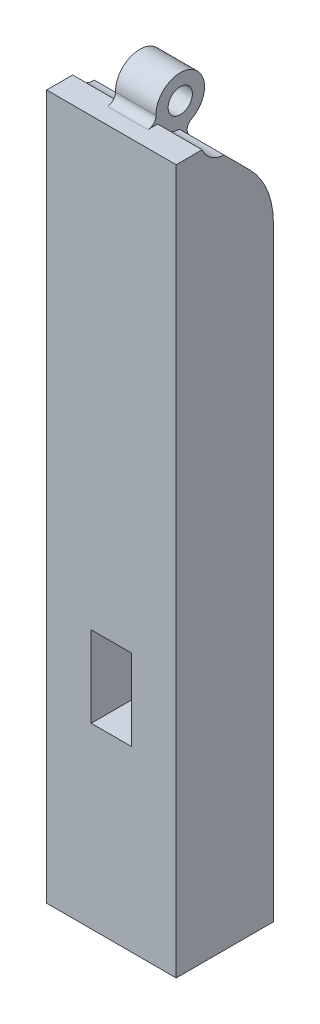
SolidWorks part; units mm, degrees
ref_plane "Front Plane" through (0, 0, 0) normal (0, 0, 1) x (1, 0, 0)
ref_plane "Top Plane" through (0, 0, 0) normal (0, 1, 0) x (1, 0, 0)
ref_plane "Right Plane" through (0, 0, 0) normal (1, 0, 0) x (0, 0, -1)
sketch "Sketch1" plane through (0, 0, 0) normal (0, 0, 1) x (1, 0, 0)
  line L1 (-8, 23.9082) -> (8, 23.9082)
  line L2 (-8, 23.9082) -> (-8, -63.0918)
  line L3 (-8, -63.0918) -> (8, -63.0918)
  line L4 (8, 23.9082) -> (8, -63.0918)
  point P4 (0, 23.9082)
extrude "Boss-Extrude2" add sketch "Sketch1" along normal blind 12
sketch "Sketch2" plane through (0, 0, 0) normal (1, 0, 0) x (0, 0, -1)
  line L0 (-12, 23.9082) -> (-8, 23.9082)
  line L1 (-12, 23.9082) -> (0, 23.9082) construction
  line L2 (0, -63.0918) -> (0, 23.9082) construction
  line L7 (-8, 23.9082) -> (0, 15.9082)
  line L8 (0, 15.9082) -> (0, 23.9082)
  line L9 (0, 23.9082) -> (-8, 23.9082)
extrude "Cut-Extrude1" cut sketch "Sketch2" against normal through all both and the other way through all contours L8 L9 L7
sketch "Sketch3" plane through (0, 0, 0) normal (1, 0, 0) x (0, 0, -1)
  line L0 (-12, 23.9082) -> (0, 23.9082)
  line L1 (-6, 23.9082) -> (-6, 25.0082)
  circle A0 centre (-6, 25.0082) radius 1.5
  circle A1 centre (-6, 25.0082) radius 3
extrude "Cut-Extrude2" cut sketch "Sketch3" against normal through all both and the other way through all contours L0 A1 A0 | L0 A1 A0
sketch "Sketch4" plane through (0, 0, 0) normal (1, 0, 0) x (0, 0, -1)
  circle A0 centre (-6, 25.0082) radius 1.5
  circle A1 centre (-6, 25.0082) radius 3
extrude "Boss-Extrude3" add sketch "Sketch4" along normal mid plane 5
fillet "Fillet1" radius 1 2 edges at (0, 23.9082, 8.7911) (0, 22.0099, 6.1017)
fillet "Fillet2" radius 10 1 edges at (0, 15.9082, 0)
sketch "Sketch5" plane through (0, 0, 0) normal (0, 0, -1) x (-1, 0, 0)
  line L0 (0, -63.0918) -> (0, -26.0918)
  line L1 (8, -63.0918) -> (-8, -63.0918) construction
  line L3 (-2.5, -21.0918) -> (2.5, -21.0918)
  line L4 (-2.5, -21.0918) -> (-2.5, -31.0918)
  line L5 (-2.5, -31.0918) -> (2.5, -31.0918)
  line L6 (2.5, -21.0918) -> (2.5, -31.0918)
  line L7 (-2.5, -21.0918) -> (2.5, -31.0918) construction
  line L8 (-2.5, -31.0918) -> (2.5, -21.0918) construction
  line L9 (-2.5, -31.0918) -> (2.5, -31.0918)
  line L10 (-2.5, -31.0918) -> (-2.5, -41.0918)
  line L11 (-2.5, -41.0918) -> (2.5, -41.0918)
  line L12 (2.5, -31.0918) -> (2.5, -41.0918)
  line L13 (-2.5, -21.0918) -> (2.5, -21.0918)
  line L14 (-2.5, -21.0918) -> (-2.5, -11.0918)
  line L15 (-2.5, -11.0918) -> (2.5, -11.0918)
  line L16 (2.5, -21.0918) -> (2.5, -11.0918)
extrude "Cut-Extrude3" cut sketch "Sketch5" against normal blind 5 contours L3 L16 L15 L14 | L12 L5 L0 L11 | L10 L11 L0 L5
sketch "Sketch6" plane through (0, -31.0918, 0) normal (0, -1, 0) x (1, 0, 0)
  line L0 (-2.5, 5) -> (-2.5, 0) construction
  line L1 (2.5, 5) -> (-2.5, 5)
  line L2 (2.5, 5) -> (2.5, 2.5)
  line L3 (2.5, 2.5) -> (-2.5, 2.5)
  line L4 (-2.5, 5) -> (-2.5, 2.5)
extrude "Cut-Extrude4" cut sketch "Sketch6" against normal up to next
sketch "Sketch7" plane through (0, 0, 0) normal (0, 0, -1) x (-1, 0, 0)
  line L1 (-2.5, -31.0918) -> (2.5, -31.0918)
  line L2 (-2.5, -31.0918) -> (-2.5, -41.0918)
  line L3 (-2.5, -41.0918) -> (2.5, -41.0918)
  line L4 (2.5, -31.0918) -> (2.5, -41.0918)
extrude "Cut-Extrude5" cut sketch "Sketch7" against normal through all
